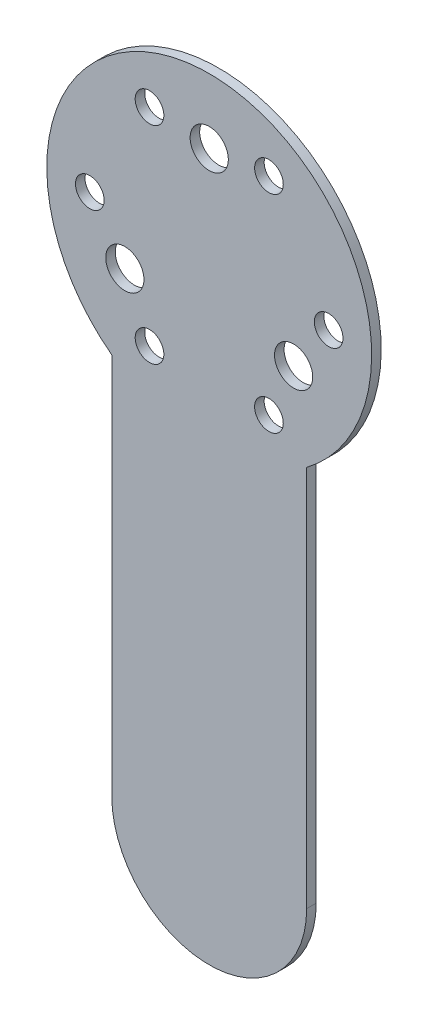
SolidWorks part; units mm, degrees
ref_plane "Front Plane" through (0, 0, 0) normal (0, 0, 1) x (1, 0, 0)
ref_plane "Top Plane" through (0, 0, 0) normal (0, 1, 0) x (1, 0, 0)
ref_plane "Right Plane" through (0, 0, 0) normal (1, 0, 0) x (0, 0, -1)
sketch "Sketch2" plane through (0, 0, 0) normal (0, 0, 1) x (1, 0, 0)
  line L0 (-10.2, -13.6) -> (-10.2, -53.6)
  line L1 (10.2, -13.6) -> (10.2, -53.6)
  arc A2 (10.2, -13.6) -> (-10.2, -13.6) centre (0, 0) ccw
  arc A3 (-10.2, -53.6) -> (10.2, -53.6) centre (0, -53.6) ccw
  circle A4 centre (0, 10.2) radius 2
  circle A5 centre (8.8335, -5.1) radius 2
  circle A6 centre (-8.8335, -5.1) radius 2
  circle A7 centre (-12.5, 0) radius 1.5
  circle A8 centre (-6.25, 10.8253) radius 1.5
  circle A9 centre (6.25, 10.8253) radius 1.5
  circle A10 centre (12.5, 0) radius 1.5
  circle A11 centre (6.25, -10.8253) radius 1.5
  circle A12 centre (-6.25, -10.8253) radius 1.5
  point P17 (0, 0)
  point P31 (0, 0)
  dimension "D1" = 3
  dimension "D2" = 6
extrude "Boss-Extrude2" add sketch "Sketch2" along normal blind 1
